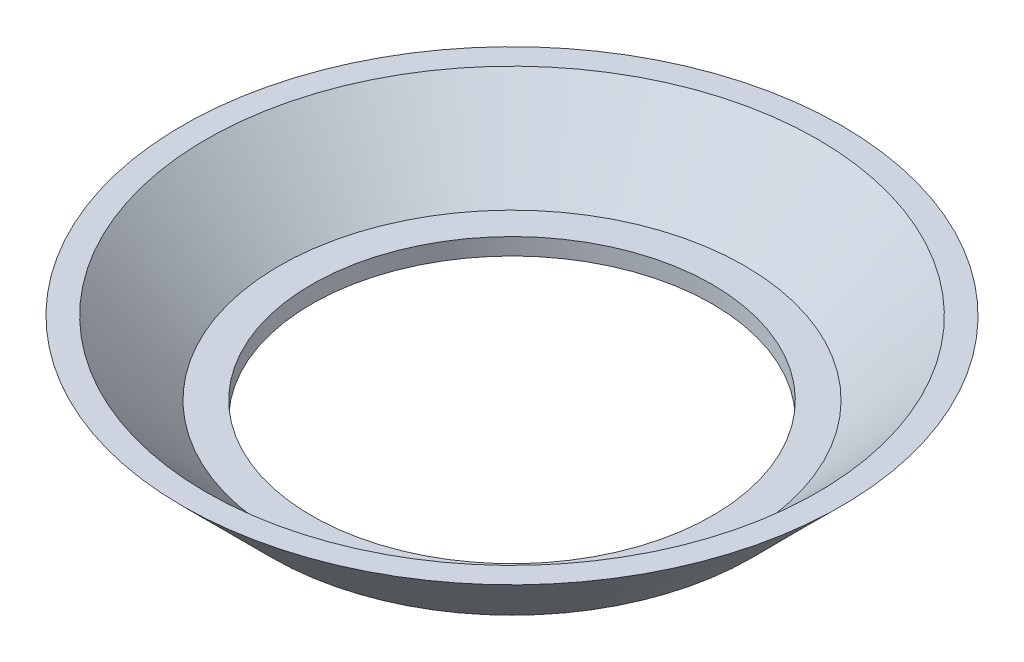
SolidWorks part; units mm, degrees
ref_plane "Ebene vorne" through (0, 0, 0) normal (0, 0, 1) x (1, 0, 0)
ref_plane "Ebene oben" through (0, 0, 0) normal (0, 1, 0) x (1, 0, 0)
ref_plane "Ebene rechts" through (0, 0, 0) normal (1, 0, 0) x (0, 0, -1)
sketch "Skizze1" plane through (0, 0, 0) normal (0, 0, 1) x (1, 0, 0)
  line L0 (35.66, 0) -> (42.66, 0)
  line L1 (55, 0) -> (-55, 0) construction
  line L2 (42.66, 0) -> (58.66, 16)
  line L3 (58.66, 16) -> (54.4174, 16)
  line L4 (54.4174, 16) -> (41.4174, 3)
  line L5 (41.4174, 3) -> (35.66, 3)
  line L6 (35.66, 3) -> (35.66, 0)
  line L7 (0, -7.7986) -> (0, 17.576) construction
  dimension "D1" = 90
  dimension "D2" = 3
  dimension "D3" = 3
  dimension "D4" = 35.66
  dimension "D5" = 7
  dimension "D6" = 16
  dimension "D7" = 135
revolve "Rotation1" add sketch "Skizze1" angle 360 about L7
